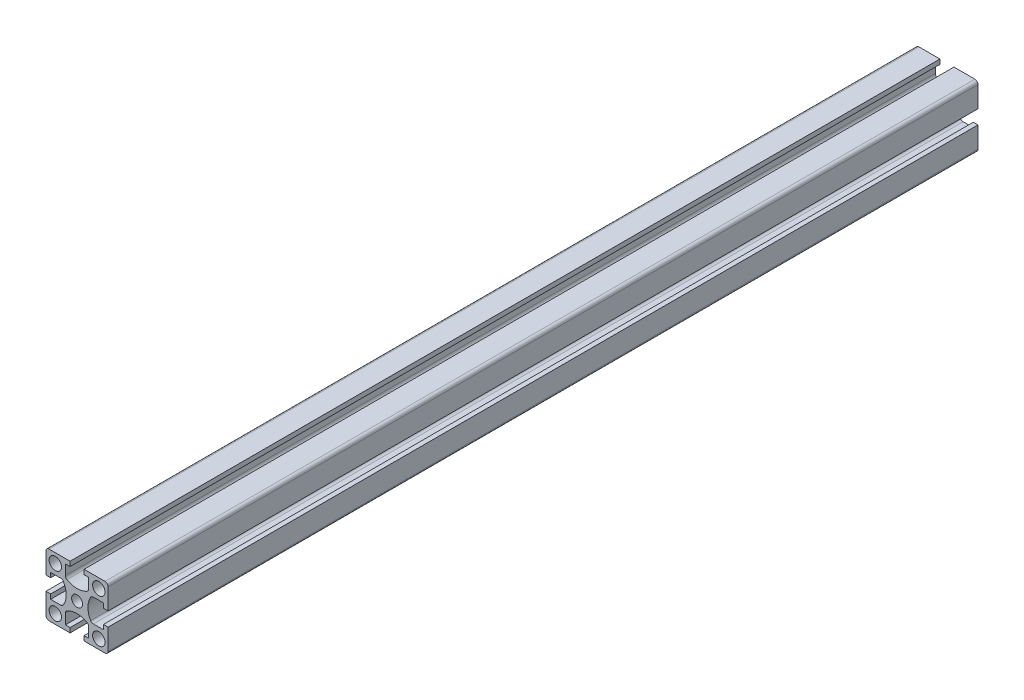
SolidWorks part; units mm, degrees
ref_plane "Front Plane" through (0, 0, 0) normal (0, 0, 1) x (1, 0, 0)
ref_plane "Top Plane" through (0, 0, 0) normal (0, 1, 0) x (1, 0, 0)
ref_plane "Right Plane" through (0, 0, 0) normal (1, 0, 0) x (0, 0, -1)
sketch "Sketch1" plane through (0, 0, 0) normal (0, 0, 1) x (1, 0, 0)
  line L64 (-25, 22.5) -> (-25, 5.625)
  line L65 (-25, 5.625) -> (-21.25, 5.625)
  line L66 (-21.25, 5.625) -> (-21.25, 9.375)
  line L67 (-21.25, 9.375) -> (-13.0922, 9.375)
  line L68 (-13.0922, -9.375) -> (-21.25, -9.375)
  line L69 (-21.25, -9.375) -> (-21.25, -5.625)
  line L70 (-21.25, -5.625) -> (-25, -5.625)
  line L71 (-25, -5.625) -> (-25, -22.5)
  line L72 (-22.5, -25) -> (-5.625, -25)
  line L73 (-5.625, -25) -> (-5.625, -21.25)
  line L74 (-5.625, -21.25) -> (-9.375, -21.25)
  line L75 (-9.375, -21.25) -> (-9.375, -13.0922)
  line L76 (9.375, -13.0922) -> (9.375, -21.25)
  line L77 (9.375, -21.25) -> (5.625, -21.25)
  line L78 (5.625, -21.25) -> (5.625, -25)
  line L79 (5.625, -25) -> (22.5, -25)
  line L80 (25, -22.5) -> (25, -5.625)
  line L81 (25, -5.625) -> (21.25, -5.625)
  line L82 (21.25, -5.625) -> (21.25, -9.375)
  line L83 (21.25, -9.375) -> (13.0922, -9.375)
  line L84 (13.0922, 9.375) -> (21.25, 9.375)
  line L85 (21.25, 9.375) -> (21.25, 5.625)
  line L86 (21.25, 5.625) -> (25, 5.625)
  line L87 (25, 5.625) -> (25, 22.5)
  line L88 (22.5, 25) -> (5.625, 25)
  line L89 (5.625, 25) -> (5.625, 21.25)
  line L90 (5.625, 21.25) -> (9.375, 21.25)
  line L91 (9.375, 21.25) -> (9.375, 13.0922)
  line L92 (-9.375, 13.0922) -> (-9.375, 21.25)
  line L93 (-9.375, 21.25) -> (-5.625, 21.25)
  line L94 (-5.625, 21.25) -> (-5.625, 25)
  line L95 (-5.625, 25) -> (-22.5, 25)
  circle A5 centre (-17.5, -17.5) radius 5
  circle A6 centre (17.5, -17.5) radius 5
  circle A7 centre (17.5, 17.5) radius 5
  circle A8 centre (0, 0) radius 4.375
  circle A9 centre (-17.5, 17.5) radius 5
  arc A32 (-22.5, 25) -> (-25, 22.5) centre (-22.5, 22.5) ccw
  arc A33 (-10.9271, 8.125) -> (-13.0922, 9.375) centre (-13.0922, 6.875) ccw
  arc A34 (-10.9271, -8.125) -> (-10.9271, 8.125) centre (-25, 0) ccw
  arc A35 (-13.0922, -9.375) -> (-10.9271, -8.125) centre (-13.0922, -6.875) ccw
  arc A36 (-25, -22.5) -> (-22.5, -25) centre (-22.5, -22.5) ccw
  arc A37 (-8.125, -10.9271) -> (-9.375, -13.0922) centre (-6.875, -13.0922) ccw
  arc A38 (8.125, -10.9271) -> (-8.125, -10.9271) centre (0, -25) ccw
  arc A39 (9.375, -13.0922) -> (8.125, -10.9271) centre (6.875, -13.0922) ccw
  arc A40 (22.5, -25) -> (25, -22.5) centre (22.5, -22.5) ccw
  arc A41 (10.9271, -8.125) -> (13.0922, -9.375) centre (13.0922, -6.875) ccw
  arc A42 (10.9271, 8.125) -> (10.9271, -8.125) centre (25, 0) ccw
  arc A43 (13.0922, 9.375) -> (10.9271, 8.125) centre (13.0922, 6.875) ccw
  arc A44 (25, 22.5) -> (22.5, 25) centre (22.5, 22.5) ccw
  arc A45 (8.125, 10.9271) -> (9.375, 13.0922) centre (6.875, 13.0922) ccw
  arc A46 (-8.125, 10.9271) -> (8.125, 10.9271) centre (0, 25) ccw
  arc A47 (-9.375, 13.0922) -> (-8.125, 10.9271) centre (-6.875, 13.0922) ccw
  dimension "D3" = 10
  dimension "D4" = 8.75
  dimension "D8" = 16.25
  dimension "D9" = 2.5
  dimension "D15" = 16.25
  dimension "D1" = 50
  dimension "D2" = 50
  dimension "D5" = 19.375
  dimension "D6" = 19.375
  dimension "D7" = 3.75
  dimension "D10" = 8.1578
  dimension "D11" = 3.75
  dimension "D12" = 8.1578
  dimension "D13" = 3.75
  dimension "D14" = 3.75
extrude "Boss-Extrude1" add sketch "Sketch1" along normal blind 700
